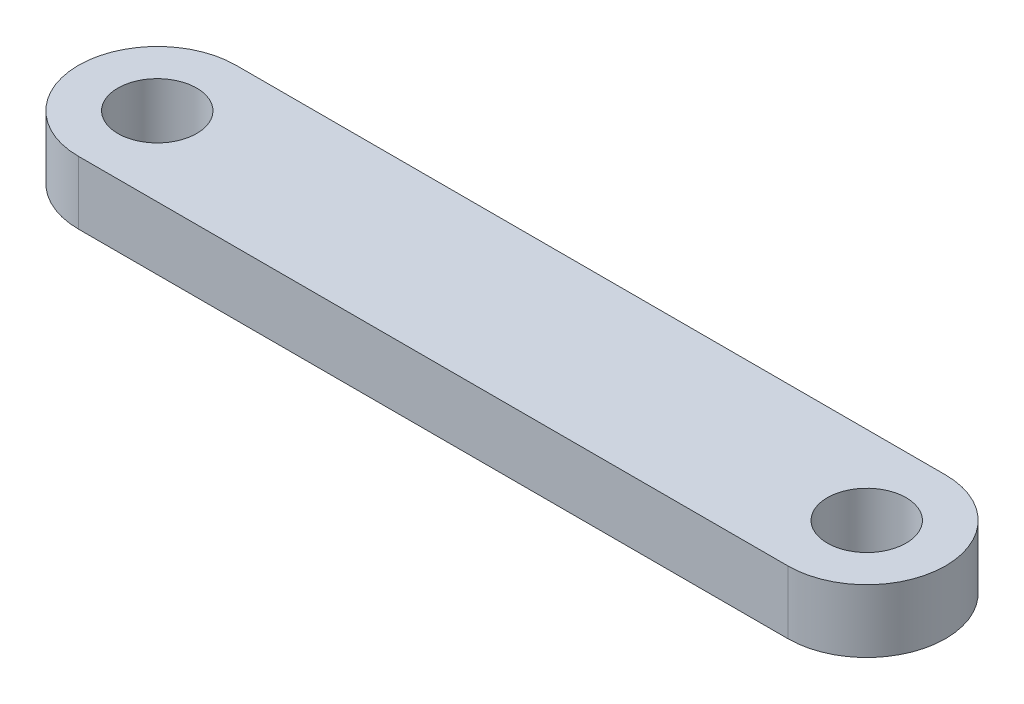
SolidWorks part; units mm, degrees
material "6061-T6 (SS)"
ref_plane "Front Plane" through (0, 0, 0) normal (0, 0, 1) x (1, 0, 0)
ref_plane "Top Plane" through (0, 0, 0) normal (0, 1, 0) x (1, 0, 0)
ref_plane "Right Plane" through (0, 0, 0) normal (1, 0, 0) x (0, 0, -1)
sketch "Sketch1" plane through (0, 0, 0) normal (0, 1, 0) x (1, 0, 0)
  line L0 (0, 0) -> (-45, 0) construction
  line L1 (0, -5) -> (-45, -5)
  line L2 (0, 5) -> (-45, 5)
  line L3 (-22.5, 5) -> (-22.5, -5) construction
  arc A0 (0, -5) -> (0, 5) centre (0, 0) ccw
  arc A1 (-45, 5) -> (-45, -5) centre (-45, 0) ccw
  circle A2 centre (-45, 0) radius 2.5
  circle A3 centre (0, 0) radius 2.5
  point P3 (-22.5, 0)
  dimension "D2" = 5
  dimension "D3" = 5
  dimension "D1" = 45
extrude "Boss-Extrude1" add sketch "Sketch1" along normal blind 4
